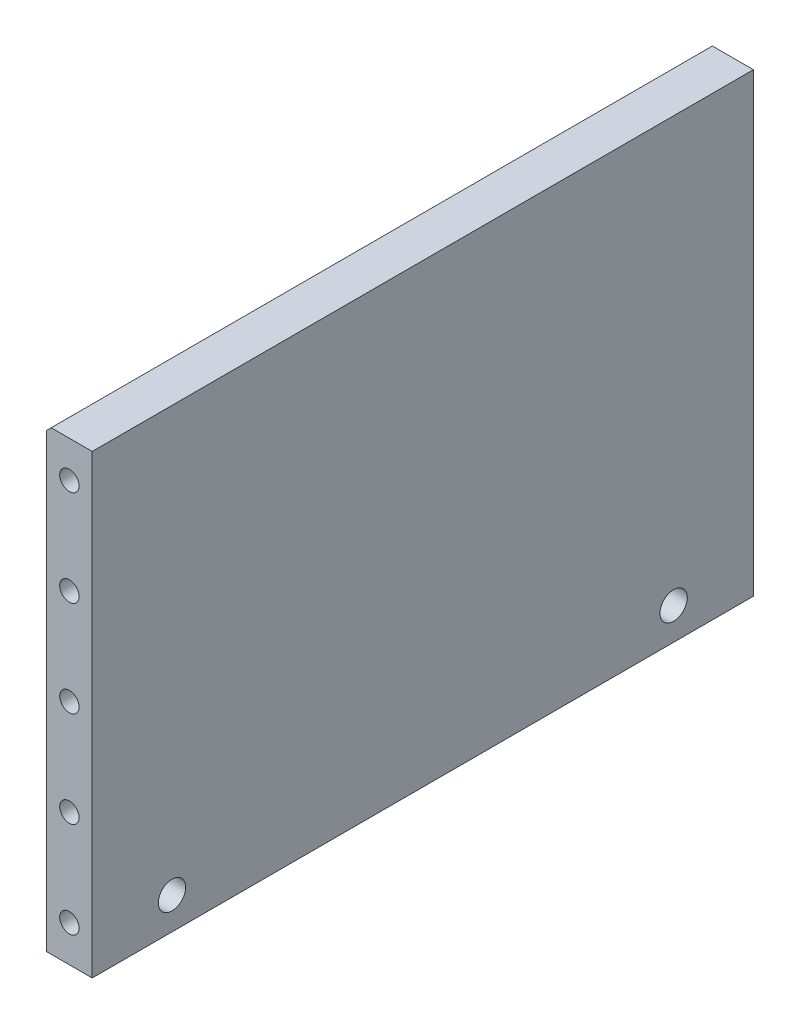
SolidWorks part; units mm, degrees
material "Carburized and nitrided special steel"
ref_plane "Piano frontale" through (0, 0, 0) normal (0, 0, 1) x (1, 0, 0)
ref_plane "Piano superiore" through (0, 0, 0) normal (0, 1, 0) x (1, 0, 0)
ref_plane "Piano destro" through (0, 0, 0) normal (1, 0, 0) x (0, 0, -1)
sketch "Schizzo1" plane through (0, 0, 0) normal (1, 0, 0) x (0, 0, -1)
  line L1 (0, 0) -> (290, 0)
  line L2 (0, 0) -> (0, 200)
  line L3 (0, 200) -> (290, 200)
  line L4 (290, 0) -> (290, 200)
  dimension "D1" = 290
  dimension "D2" = 200
extrude "Estrusione1" add sketch "Schizzo1" along normal blind 20
hole_wizard "M10 Tapped Hole1" positions "Schizzo3" profile "Schizzo2" tap size "M10" standard "ISO"
sketch "Schizzo3" plane through (0, 0, 0) normal (0, 0, 1) x (1, 0, 0)
  line L0 (0, 200) -> (0, 0) construction
  line L1 (20, 200) -> (0, 200) construction
  line L2 (20, 0) -> (0, 0) construction
  point P0 (10, 184)
  point P6 (10, 16)
  point P8 (10, 58)
  point P10 (10, 142)
  point P15 (10, 100)
  dimension "D1" = 10
  dimension "D2" = 16
  dimension "D3" = 10
  dimension "D4" = 10
  dimension "D5" = 10
  dimension "D6" = 16
  dimension "D7" = 42
  dimension "D8" = 10
  dimension "D9" = 42
  dimension "D10" = 42
  dimension "D11" = 42
sketch "Schizzo2" plane through (10, 184, 0) normal (1, 0, 0) x (0, -1, 0)
  line L0 (0, 0) -> (0, 30.0537)
  line L1 (0, 30.0537) -> (4.25, 27.5)
  line L2 (4.25, 27.5) -> (4.25, 0)
  line L5 (4.25, 0) -> (0, 0)
  line L10 (0, 30.0537) -> (-4.25, 27.5) construction
  line L11 (0, -6.35) -> (0, 107.95) construction
  dimension "Tap Drill Dia." = 8.5
  dimension "Tap Drill Depth" = 27.5
  dimension "Drill Angle" = 118
cosmetic thread "Filettatura del foro3" parameters "D1"=20, "D2"=10
cosmetic thread "Filettatura del foro4" parameters "D1"=20, "D2"=10
cosmetic thread "Filettatura del foro5" parameters "D1"=20, "D2"=10
cosmetic thread "Filettatura del foro6" parameters "D1"=20, "D2"=10
cosmetic thread "Filettatura del foro7" parameters "D1"=20, "D2"=10
ref_plane "Piano1" through (0, 0, -145) normal (0, 0, 1) x (1, 0, 0)
mirror "Specchia1" about plane through (0, 0, -145) normal (0, 0, 1) of "M10 Tapped Hole1"
hole_wizard "M14 Tapped Hole1" positions "Schizzo5" profile "Schizzo4" tap size "M14" standard "ISO"
sketch "Schizzo5" plane through (20, 0, 0) normal (1, 0, 0) x (0, 0, -1)
  line L0 (0, 0) -> (290, 0) construction
  line L1 (0, 200) -> (0, 0) construction
  line L2 (290, 0) -> (290, 200) construction
  point P0 (35, 14)
  point P1 (255, 14)
  dimension "D1" = 14
  dimension "D2" = 14
  dimension "D3" = 35
  dimension "D4" = 35
sketch "Schizzo4" plane through (20, 14, -35) normal (0, 1, 0) x (0, 0, -1)
  line L0 (0, 0) -> (0, 41.6052)
  line L1 (0, 41.6052) -> (6, 38)
  line L2 (6, 38) -> (6, 0)
  line L5 (6, 0) -> (0, 0)
  line L10 (0, 41.6052) -> (-6, 38) construction
  line L11 (0, -6.35) -> (0, 107.95) construction
  dimension "Tap Drill Dia." = 12
  dimension "Tap Drill Depth" = 38
  dimension "Drill Angle" = 118
cosmetic thread "Filettatura del foro1" parameters "D1"=20, "D2"=14
cosmetic thread "Filettatura del foro2" parameters "D1"=20, "D2"=14
chamfer "Smusso1" distance 2 angle 45 1 edges at (0, 200, -145)
